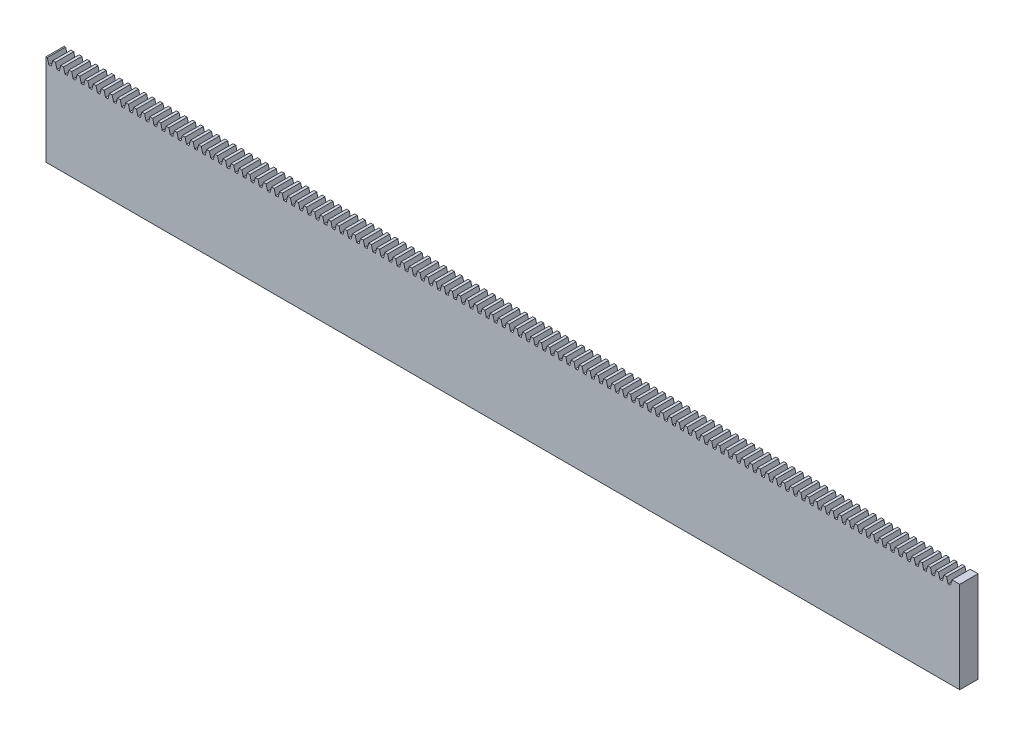
SolidWorks part; units mm, degrees
material "Brass"
ref_plane "Front Plane" through (0, 0, 0) normal (0, 0, 1) x (1, 0, 0)
ref_plane "Top Plane" through (0, 0, 0) normal (0, 1, 0) x (1, 0, 0)
ref_plane "Right Plane" through (0, 0, 0) normal (1, 0, 0) x (0, 0, -1)
sketch "Sketch1" plane through (0, 0, 0) normal (0, 0, 1) x (1, 0, 0)
  line L0 (0, 0) -> (300, 0)
  line L1 (300, 0) -> (300, 30)
  line L2 (300, 30) -> (0, 30)
  line L3 (0, 30) -> (0, 0)
  dimension "D1" = 300
  dimension "D2" = 30
extrude "Boss-Extrude1" add sketch "Sketch1" along normal blind 6
sketch "Sketch2" plane through (0, 0, 0) normal (0, 0, 1) x (1, 0, 0)
  line L0 (0.9183, 28.1737) -> (0.1874, 31)
  line L1 (0.1874, 31) -> (2.4725, 31)
  line L2 (2.4725, 31) -> (1.7416, 28.1737)
  line L3 (1.7416, 28.1737) -> (0.9183, 28.1737)
  dimension "D1" = 0.9183
  dimension "D2" = 28.1737
  dimension "D3" = 0.7309
  dimension "D4" = 2.8263
  dimension "D5" = 2.2851
  dimension "D6" = 0.7309
  dimension "D7" = 2.8263
extrude "Cut-Extrude2" cut sketch "Sketch2" against normal blind 7 and the other way blind 7
pattern_linear "LPattern1" count 112 spacing 2.6599 along (1, 0, 0) of "Cut-Extrude2"
